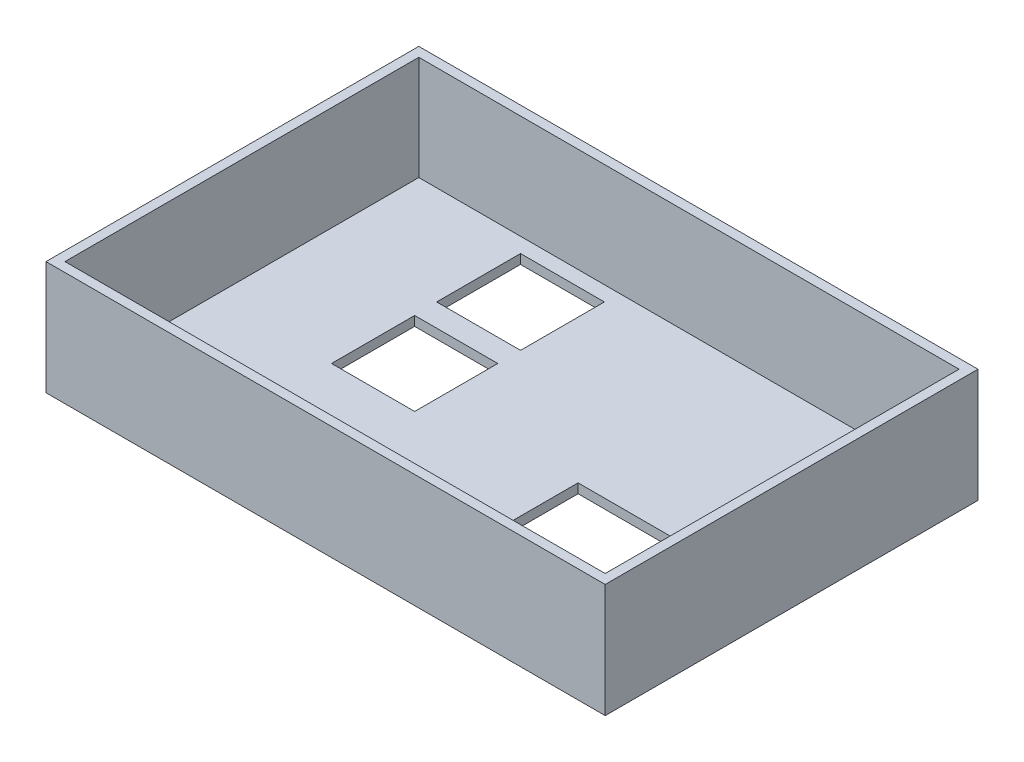
SolidWorks part; units mm, degrees
ref_plane "Front Plane" through (0, 0, 0) normal (0, 0, 1) x (1, 0, 0)
ref_plane "Top Plane" through (0, 0, 0) normal (0, 1, 0) x (1, 0, 0)
ref_plane "Right Plane" through (0, 0, 0) normal (1, 0, 0) x (0, 0, -1)
sketch "Sketch1" plane through (0, 0, 0) normal (0, 1, 0) x (1, 0, 0)
  line L1 (40.668, 31.336) -> (-109.332, 31.336)
  line L2 (40.668, 31.336) -> (40.668, -68.664)
  line L3 (40.668, -68.664) -> (-109.332, -68.664)
  line L4 (-109.332, 31.336) -> (-109.332, -68.664)
  dimension "D1" = 150
  dimension "D2" = 100
extrude "Boss-Extrude1" add sketch "Sketch1" against normal blind 30.48
shell "Shell1" thickness 2.54
sketch "Sketch3" plane through (0, -30.48, 0) normal (0, -1, 0) x (1, 0, 0)
  line L1 (-14.511, 53.1603) -> (29.5147, 53.1603)
  line L2 (-14.511, 53.1603) -> (-14.511, 20.7605)
  line L3 (-14.511, 20.7605) -> (29.5147, 20.7605)
  line L4 (29.5147, 53.1603) -> (29.5147, 20.7605)
extrude "Cut-Extrude1" cut sketch "Sketch3" against normal blind 30.48
sketch "Sketch4" plane through (0, -30.48, 0) normal (0, -1, 0) x (-1, 0, 0)
  line L1 (53.0096, -3.7982) -> (75.3083, -3.7982)
  line L2 (53.0096, -3.7982) -> (53.0096, -26.0969)
  line L3 (53.0096, -26.0969) -> (75.3083, -26.0969)
  line L4 (75.3083, -3.7982) -> (75.3083, -26.0969)
  line L5 (53.0096, -3.7982) -> (75.3083, -26.0969) construction
  line L6 (53.0096, -26.0969) -> (75.3083, -3.7982) construction
  line L7 (53.0096, 25.7428) -> (75.4988, 25.7428)
  line L8 (53.0096, 25.7428) -> (53.0096, 3.2535)
  line L9 (53.0096, 3.2535) -> (75.4988, 3.2535)
  line L10 (75.4988, 25.7428) -> (75.4988, 3.2535)
  line L11 (53.0096, 25.7428) -> (75.4988, 3.2535) construction
  line L12 (53.0096, 3.2535) -> (75.4988, 25.7428) construction
  point P0 (64.1589, -14.9476)
  point P5 (64.2542, 14.4981)
extrude "Cut-Extrude2" cut sketch "Sketch4" against normal blind 30.48 contours L2 L1 L4 L3
sketch "Sketch5" plane through (0, -30.48, 0) normal (0, -1, 0) x (1, 0, 0)
  line L1 (-53.0096, -24.7898) -> (-75.4988, -24.7898)
  line L2 (-53.0096, -24.7898) -> (-53.0096, -2.3005)
  line L3 (-53.0096, -2.3005) -> (-75.4988, -2.3005)
  line L4 (-75.4988, -24.7898) -> (-75.4988, -2.3005)
  line L5 (-53.0096, -24.7898) -> (-75.4988, -2.3005) construction
  line L6 (-53.0096, -2.3005) -> (-75.4988, -24.7898) construction
  point P0 (-64.2542, -13.5452)
extrude "Cut-Extrude3" cut sketch "Sketch5" against normal blind 30.48
